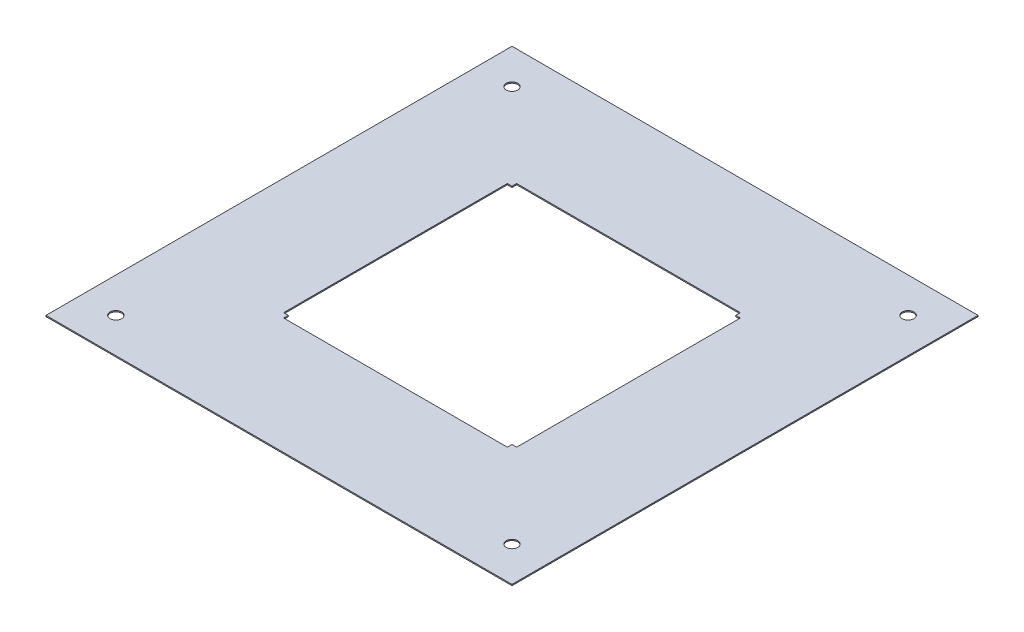
SolidWorks part; units mm, degrees
ref_plane "Alzado" through (0, 0, 0) normal (0, 0, 1) x (1, 0, 0)
ref_plane "Planta" through (0, 0, 0) normal (0, 1, 0) x (1, 0, 0)
ref_plane "Vista lateral" through (0, 0, 0) normal (1, 0, 0) x (0, 0, -1)
sketch "Croquis1" plane through (0, 0, 0) normal (0, 1, 0) x (1, 0, 0)
  line L0 (100, 15) -> (100, 0) construction
  line L1 (0, 0) -> (200, 0)
  line L2 (0, 0) -> (0, 200)
  line L3 (0, 200) -> (200, 200)
  line L4 (200, 0) -> (200, 200)
  line L5 (15, 15) -> (185, 15) construction
  line L6 (15, 15) -> (15, 185) construction
  line L7 (15, 185) -> (185, 185) construction
  line L8 (185, 15) -> (185, 185) construction
  line L9 (185, 100) -> (200, 100) construction
  circle A0 centre (15, 185) radius 2.5
  circle A1 centre (185, 185) radius 2.5
  circle A2 centre (185, 15) radius 2.5
  circle A3 centre (15, 15) radius 2.5
  dimension "D3" = 5
  dimension "D1" = 200
  dimension "D2" = 170
extrude "Saliente-Extruir1" add sketch "Croquis1" along normal blind 0.5
sketch "Croquis2" plane through (0, 0.5, 0) normal (0, 1, 0) x (1, 0, 0)
  line L0 (100, 0) -> (100, 200) construction
  line L1 (0, 0) -> (200, 0) construction
  line L2 (200, 200) -> (0, 200) construction
  line L3 (0, 100) -> (200, 100) construction
  line L4 (0, 200) -> (0, 0) construction
  line L5 (200, 0) -> (200, 200) construction
  line L6 (50, 148) -> (50, 100)
  line L7 (50, 150) -> (150, 150) construction
  line L8 (50, 150) -> (50, 50) construction
  line L9 (50, 50) -> (150, 50) construction
  line L10 (150, 150) -> (150, 50) construction
  line L13 (50, 148) -> (52, 148)
  line L14 (52, 150) -> (52, 148)
  line L15 (52, 150) -> (100, 150)
  line L16 (150, 148) -> (150, 100)
  line L17 (150, 148) -> (148, 148)
  line L18 (148, 150) -> (148, 148)
  line L19 (148, 150) -> (100, 150)
  line L20 (148, 50) -> (100, 50)
  line L21 (148, 50) -> (148, 52)
  line L22 (150, 52) -> (148, 52)
  line L23 (150, 52) -> (150, 100)
  line L24 (50, 52) -> (50, 100)
  line L25 (50, 52) -> (52, 52)
  line L26 (52, 50) -> (52, 52)
  line L27 (52, 50) -> (100, 50)
  point P16 (100, 150)
  point P17 (50, 100)
  point P23 (148, 100)
  point P25 (45.6835, 152.5332)
  dimension "D1" = 2
  dimension "D3" = 100
  dimension "D2" = 4
extrude "Cortar-Extruir1" cut sketch "Croquis2" against normal blind 10
